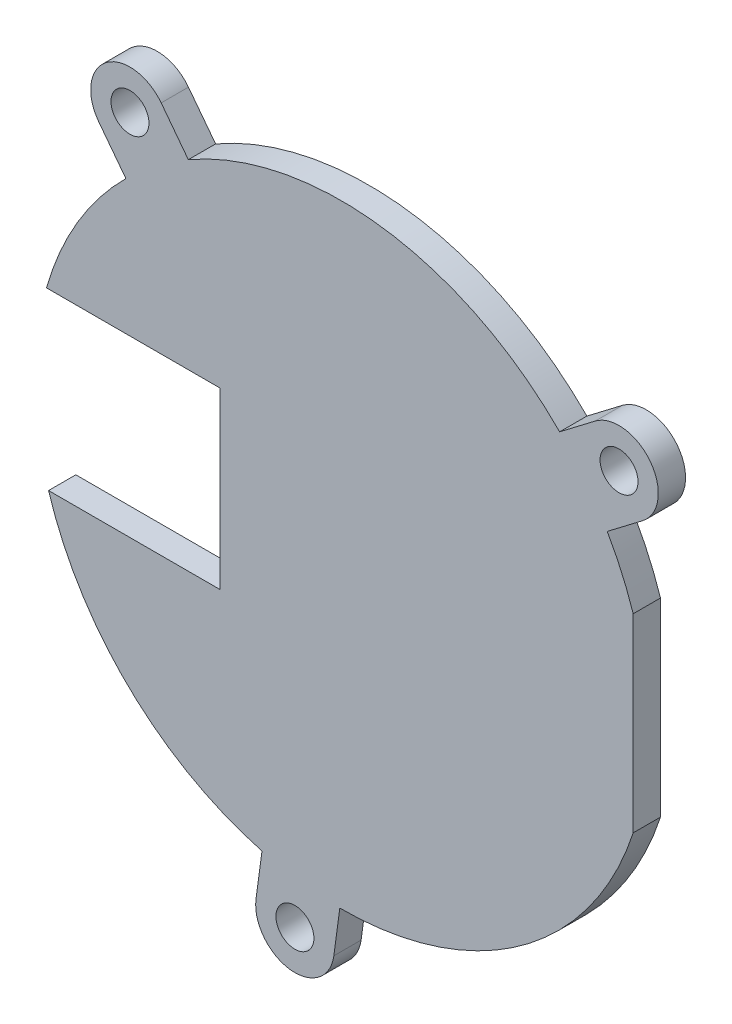
SolidWorks part; units mm, degrees
ref_plane "Front Plane" through (0, 0, 0) normal (0, 0, 1) x (1, 0, 0)
ref_plane "Top Plane" through (0, 0, 0) normal (0, 1, 0) x (1, 0, 0)
ref_plane "Right Plane" through (0, 0, 0) normal (1, 0, 0) x (0, 0, -1)
sketch "Sketch1" plane through (0, 0, 0) normal (0, 0, 1) x (1, 0, 0)
  line L0 (-7.085, 4.8768) -> (-17.1812, 4.8768) construction
  line L1 (-7.085, 4.8768) -> (-7.085, -5.2832) construction
  line L2 (-17.0607, -5.2832) -> (-7.085, -5.2832) construction
  line L3 (-4.9801, -19.8325) -> (-4.6318, -17.2489) construction
  line L4 (-0.1008, -17.8597) -> (-0.449, -20.4433) construction
  line L5 (16.9841, -5.5245) -> (16.9841, 5.5245) construction
  line L6 (17.5451, 10.5023) -> (15.472, 8.9216) construction
  line L7 (14.7731, 14.138) -> (12.7, 12.5574) construction
  line L8 (-8.9216, 15.472) -> (-10.5023, 17.5451) construction
  line L9 (-14.138, 14.7731) -> (-12.5574, 12.7) construction
  line L10 (-7.085, 4.8768) -> (-17.1812, 4.8768)
  line L11 (-7.085, 4.8768) -> (-7.085, -5.2832)
  line L12 (-17.0607, -5.2832) -> (-7.085, -5.2832)
  line L13 (-4.9801, -19.8325) -> (-4.6318, -17.2489)
  line L14 (-0.1008, -17.8597) -> (-0.449, -20.4433)
  line L15 (16.9841, -5.5245) -> (16.9841, 5.5245)
  line L16 (17.5451, 10.5023) -> (15.472, 8.9216)
  line L17 (14.7731, 14.138) -> (12.7, 12.5574)
  line L18 (-8.9216, 15.472) -> (-10.5023, 17.5451)
  line L19 (-14.138, 14.7731) -> (-12.5574, 12.7)
  arc A0 (-17.0607, -5.2832) -> (-4.6318, -17.2489) centre (0, 0) ccw construction
  arc A1 (-4.9801, -19.8325) -> (-0.449, -20.4433) centre (-2.7145, -20.1379) ccw construction
  circle A2 centre (-2.7145, -20.1379) radius 1.1049 construction
  arc A3 (-0.1008, -17.8597) -> (16.9841, -5.5245) centre (0, 0) ccw construction
  arc A4 (16.9841, 5.5245) -> (15.472, 8.9216) centre (0, 0) ccw construction
  arc A5 (17.5451, 10.5023) -> (14.7731, 14.138) centre (16.1591, 12.3201) ccw construction
  arc A6 (12.7, 12.5574) -> (-8.9216, 15.472) centre (0, 0) ccw construction
  arc A7 (-10.5023, 17.5451) -> (-14.138, 14.7731) centre (-12.3201, 16.1591) ccw construction
  arc A8 (-12.5574, 12.7) -> (-17.1812, 4.8768) centre (0, 0) ccw construction
  arc A9 (-17.0607, -5.2832) -> (-4.6318, -17.2489) centre (0, 0) ccw
  arc A10 (-4.9801, -19.8325) -> (-0.449, -20.4433) centre (-2.7145, -20.1379) ccw
  circle A11 centre (-2.7145, -20.1379) radius 1.1049
  arc A12 (-0.1008, -17.8597) -> (16.9841, -5.5245) centre (0, 0) ccw
  arc A13 (16.9841, 5.5245) -> (15.472, 8.9216) centre (0, 0) ccw
  arc A14 (17.5451, 10.5023) -> (14.7731, 14.138) centre (16.1591, 12.3201) ccw
  arc A15 (12.7, 12.5574) -> (-8.9216, 15.472) centre (0, 0) ccw
  arc A16 (-10.5023, 17.5451) -> (-14.138, 14.7731) centre (-12.3201, 16.1591) ccw
  arc A17 (-12.5574, 12.7) -> (-17.1812, 4.8768) centre (0, 0) ccw
  circle A18 centre (-12.3201, 16.1591) radius 1.1049 construction
  circle A19 centre (16.1591, 12.3201) radius 1.1049 construction
  circle A20 centre (-12.3201, 16.1591) radius 1.1049
  circle A21 centre (16.1591, 12.3201) radius 1.1049
extrude "Boss-Extrude1" add sketch "Sketch1" along normal blind 1.5875
